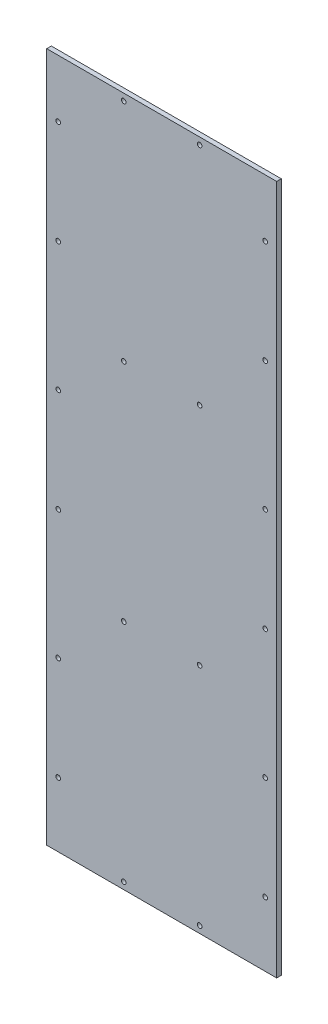
SolidWorks part; units mm, degrees
material "Alumina"
ref_plane "Front Plane" through (0, 0, 0) normal (0, 0, 1) x (1, 0, 0)
ref_plane "Top Plane" through (0, 0, 0) normal (0, 1, 0) x (1, 0, 0)
ref_plane "Right Plane" through (0, 0, 0) normal (1, 0, 0) x (0, 0, -1)
sketch "Sketch1" plane through (0, 0, 0) normal (0, 0, 1) x (1, 0, 0)
  line L1 (50, -150) -> (-50, -150)
  line L2 (50, -150) -> (50, 150)
  line L3 (50, 150) -> (-50, 150)
  line L4 (-50, -150) -> (-50, 150)
  line L5 (50, -150) -> (-50, 150) construction
  line L6 (50, 150) -> (-50, -150) construction
  point P0 (0, 0)
  dimension "D1" = 100
  dimension "D2" = 300
extrude "Boss-Extrude1" add sketch "Sketch1" along normal blind 2
sketch "Sketch2" plane through (0, 0, 2) normal (0, 0, 1) x (1, 0, 0)
  line L0 (-50, 150) -> (-50, -150) construction
  line L1 (50, 150) -> (-50, 150) construction
  line L2 (-50, -150) -> (50, -150) construction
  line L3 (50, -150) -> (50, 150) construction
  line L4 (0, -1.1) -> (0, 1.1) construction
  line L5 (-45, 125) -> (-45, 24) construction
  circle A0 centre (-45, 125) radius 1
  circle A1 centre (-45, 80) radius 1
  circle A2 centre (45, 125) radius 1
  circle A3 centre (45, 80) radius 1
  circle A4 centre (-45, 24) radius 1
  circle A5 centre (-45, -21) radius 1
  circle A6 centre (45, 24) radius 1
  circle A7 centre (45, -21) radius 1
  circle A8 centre (-45, -77) radius 1
  circle A9 centre (-45, -122) radius 1
  circle A10 centre (45, -77) radius 1
  circle A11 centre (45, -122) radius 1
  circle A13 centre (16.5, -147) radius 1
  circle A14 centre (-16.5, -147) radius 1
  circle A15 centre (-16.5, -49) radius 1
  circle A16 centre (16.5, -49) radius 1
  circle A17 centre (-16.5, 49) radius 1
  circle A18 centre (16.5, 49) radius 1
  circle A19 centre (-16.5, 147) radius 1
  circle A20 centre (16.5, 147) radius 1
  dimension "D1" = 2
  dimension "D3" = 25
  dimension "D4" = 2
  dimension "D6" = 5
  dimension "D10" = 2
  dimension "D11" = 33
  dimension "D13" = 3
  dimension "D14" = 5
  dimension "D15" = 3
  dimension "D16" = 5
  dimension "D2" = 5
  dimension "D9" = 28
  dimension "D17" = 101
  dimension "D7" = 2
  dimension "D8" = 3
  dimension "D12" = 4
extrude "Cut-Extrude1" cut sketch "Sketch2" against normal blind 25
